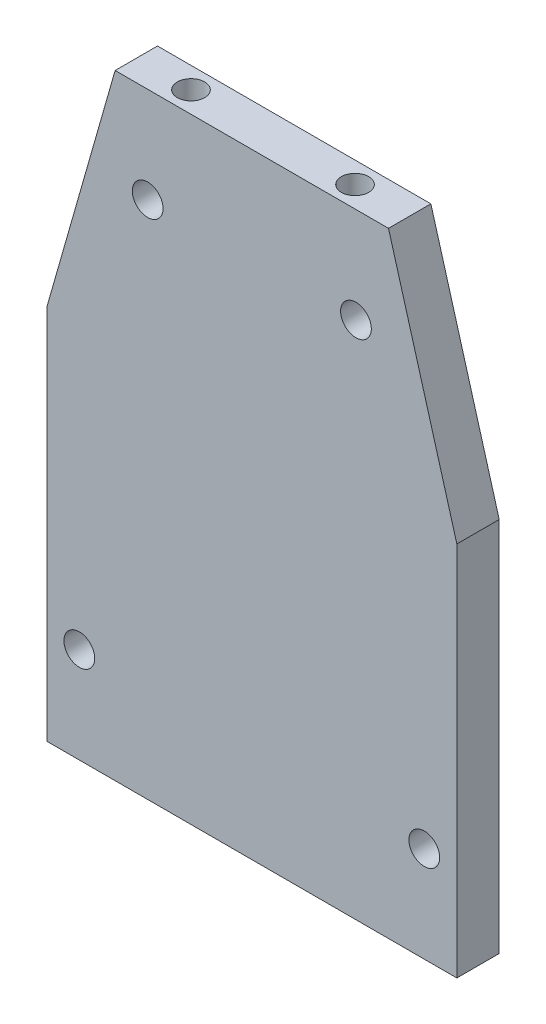
SolidWorks part; units mm, degrees
material "6061 Alloy"
ref_plane "Front Plane" through (0, 0, 0) normal (0, 0, 1) x (1, 0, 0)
ref_plane "Top Plane" through (0, 0, 0) normal (0, 1, 0) x (1, 0, 0)
ref_plane "Right Plane" through (0, 0, 0) normal (1, 0, 0) x (0, 0, -1)
sketch "Sketch1" plane through (0, 0, 0) normal (0, 0, 1) x (1, 0, 0)
  line L0 (-20, 45) -> (20, 45)
  line L5 (-30, -45) -> (30, -45)
  line L6 (0, 45) -> (0, -45) construction
  line L7 (-20, 45) -> (-30, 10)
  line L8 (-30, 10) -> (-30, -45)
  line L9 (30, 10) -> (30, -45)
  line L10 (20, 45) -> (30, 10)
  dimension "D1" = 90
  dimension "D2" = 60
  dimension "D3" = 40
  dimension "D4" = 55
extrude "1/4" add sketch "Sketch1" along normal mid plane 6.2
sketch "Sketch4" plane through (0, 45, 0) normal (0, 1, 0) x (1, 0, 0)
  line L0 (0, -3.1) -> (0, 3.1) construction
  line L1 (0, 0) -> (-12, 0) construction
  line L2 (20, -3.1) -> (-20, -3.1) construction
  line L3 (20, 3.1) -> (-20, 3.1) construction
  circle A0 centre (-12, 0) radius 2
  circle A1 centre (12, 0) radius 2
  dimension "D2" = 4
  dimension "D1" = 12
extrude "M4_DRILL" cut sketch "Sketch4" against normal blind 8
sketch "Sketch5" plane through (0, -45, 0) normal (0, -1, 0) x (-1, 0, 0)
  line L0 (0, -3.1) -> (0, 3.1) construction
  line L2 (0, 0) -> (-20, 0) construction
  line L3 (30, -3.1) -> (-30, -3.1) construction
  line L4 (30, 3.1) -> (-30, 3.1) construction
  circle A0 centre (-20, 0) radius 2
  circle A1 centre (20, 0) radius 2
  circle A2 centre (0, 0) radius 2
  dimension "D1" = 4
  dimension "D2" = 20
extrude "M4_DRILL2" cut sketch "Sketch5" against normal blind 8
sketch "Sketch6" plane through (0, 0, 3.1) normal (0, 0, 1) x (1, 0, 0)
  line L0 (-30, -45) -> (30, -45) construction
  line L1 (-30, 10) -> (-30, -45) construction
  line L2 (0, 0) -> (0, -17.9243) construction
  line L3 (20, 45) -> (-20, 45) construction
  circle A0 centre (-25.2375, -31) radius 2.25
  circle A1 centre (25.2375, -31) radius 2.25
  circle A2 centre (-15.2375, 31) radius 2.25
  circle A3 centre (15.2375, 31) radius 2.25
  dimension "D1" = 4.5
  dimension "D6" = 4.5
  dimension "D2" = 14
  dimension "D3" = 4.7625
  dimension "D4" = 14
  dimension "D5" = 4.7625
extrude "M4_through" cut sketch "Sketch6" against normal up to surface (6.2 mm away) up to face at (0, 3.3333, -3.1)
